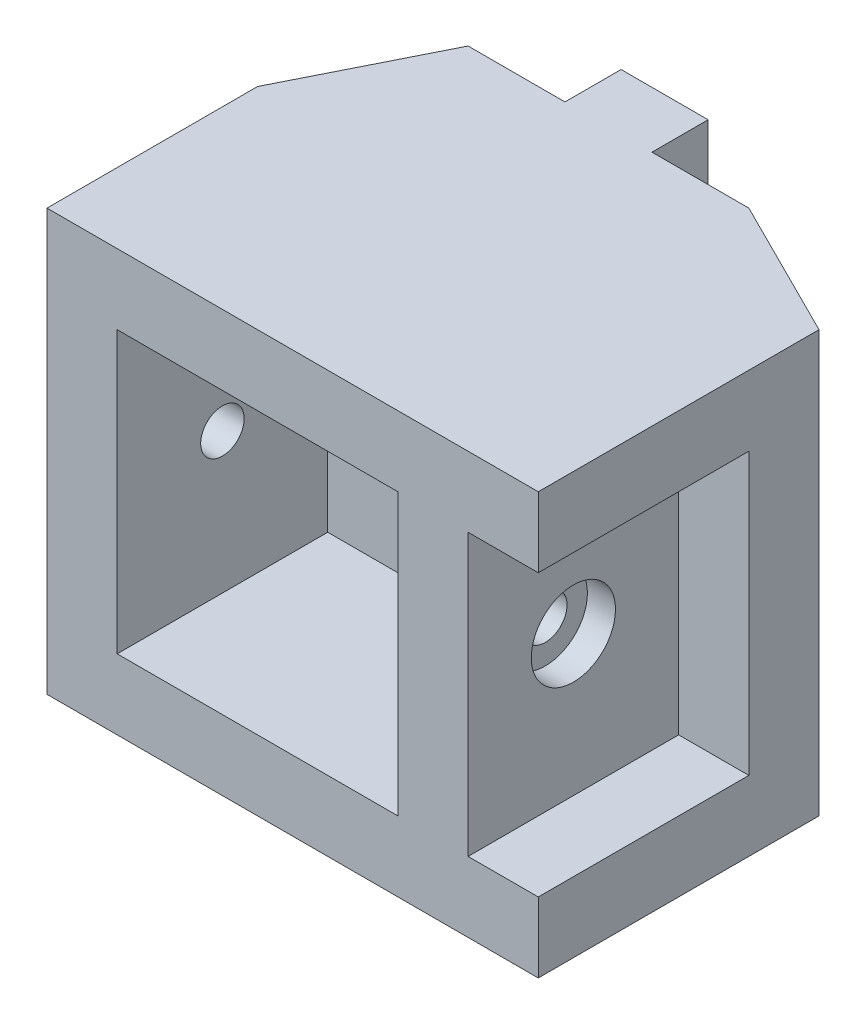
SolidWorks part; units mm, degrees
ref_plane "Front Plane" through (0, 0, 0) normal (0, 0, 1) x (1, 0, 0)
ref_plane "Top Plane" through (0, 0, 0) normal (0, 1, 0) x (1, 0, 0)
ref_plane "Right Plane" through (0, 0, 0) normal (1, 0, 0) x (0, 0, -1)
other "Configuration Table"
sketch "草图1" plane through (0, 0, 0) normal (0, 0, 1) x (1, 0, 0)
  line L0 (-15, 22) -> (-15, -22)
  line L1 (0, 22) -> (15, 22)
  line L2 (0, 22) -> (-15, 22)
  line L3 (15, 22) -> (15, -22)
  line L4 (15, -22) -> (-15, -22)
extrude "凸台-拉伸1" add sketch "草图1" along normal blind 14 contours L0 L4 L3 L1 L2
sketch "草图2" plane through (0, 22, 0) normal (0, 1, 0) x (1, 0, 0)
  line L3 (10, -4) -> (15, -14)
  line L4 (15, -14) -> (-15, -14)
  line L6 (-15, -14) -> (-10, -4)
  line L8 (3.1, -4) -> (3.1, 0)
  line L9 (-15, 0) -> (15, 0) construction
  line L10 (3.1, 0) -> (15, 0)
  line L11 (15, 0) -> (15, -14)
  line L12 (10, -4) -> (3.1, -4)
  line L13 (-3.1, -4) -> (-10, -4)
  line L14 (-15, -14) -> (-15, 0)
  line L15 (-15, 0) -> (-3.1, 0)
  line L16 (-3.1, 0) -> (-3.1, -4)
  line M14 (15, 0) -> (-15, 0)
  line M15 (-15, 0) -> (-15, -14)
  line M17 (15, -14) -> (15, 0)
extrude "切除-拉伸1" cut sketch "草图2" against normal blind 44 contours L16 L6 L13 M14 M15 | L12 L3 L8 M17 M14
sketch "草图3" plane through (0, 0, 0) normal (0, 0, -1) x (-1, 0, 0)
  line L2 (-3.1, 3.1) -> (-3.1, -3.1)
  line L4 (3.1, -22) -> (3.1, 22) construction
  line L5 (3.1, 3.1) -> (-3.1, 3.1)
  line L6 (-3.1, -22) -> (-3.1, 22) construction
  line L9 (-3.1, -3.1) -> (3.1, -3.1)
  line L10 (3.1, -22) -> (3.1, 22) construction
  line L11 (3.1, -3.1) -> (3.1, 3.1)
extrude "切除-拉伸2" cut sketch "草图3" against normal blind 4 contours L2 L9 L11 L5
sketch "草图4" plane through (0, 0, 14) normal (0, 0, 1) x (1, 0, 0)
  circle A0 centre (0, 0) radius 4
extrude "切除-拉伸3" cut sketch "草图4" against normal blind 5
sketch "草图5" plane through (0, 0, 9) normal (0, 0, 1) x (1, 0, 0)
  circle A0 centre (0, 0) radius 2.6
extrude "切除-拉伸4" cut sketch "草图5" against normal blind 5 contours A0
sketch "草图7" plane through (0, -22, 0) normal (0, -1, 0) x (1, 0, 0)
  line L3 (10, 4) -> (3.1, 4) construction
  line L5 (15, 14) -> (20, 14)
  line L8 (10, 4) -> (20, 9)
  line L9 (20, 9) -> (20, 14)
  line L10 (10, 4) -> (10, 14)
  line L11 (15, 14) -> (-15, 14) construction
  line L12 (10, 14) -> (15, 14)
extrude "凸台-拉伸2" add sketch "草图7" against normal blind 44 contours L12 L5 L9 L8 L10
sketch "草图8" plane through (0, 0, 14) normal (0, 0, 1) x (1, 0, 0)
  line L2 (-10, 10) -> (-10, 15)
  line L3 (-10, 10) -> (-15, 10)
  line L4 (0, 10) -> (10, 10)
  line L5 (10, 10) -> (10, 0)
  line L6 (0, -10) -> (10, -10)
  line L7 (10, -10) -> (10, 0)
  line L8 (0, -10) -> (-10, -10)
  line L9 (-10, -10) -> (-10, 0)
  line L10 (0, 10) -> (-10, 10)
  line L11 (-10, 10) -> (-10, 0)
  line L12 (-10, -10) -> (-10, -15)
  line L13 (-10, -10) -> (-15, -10)
  line L14 (10, -10) -> (15, -10)
  line L15 (10, -10) -> (10, -15)
  line L16 (10, 10) -> (10, 15)
  line L17 (10, 10) -> (15, 10)
  line L18 (-10, -15) -> (10, -15)
  line L19 (10, -15) -> (15, -15)
  line L20 (15, -15) -> (15, -10)
  line L21 (-15, -10) -> (-15, 10)
  line L22 (-10, 15) -> (10, 15)
  line L23 (15, 10) -> (15, 15)
  line L24 (15, 15) -> (10, 15)
  line L25 (15, 10) -> (15, -10)
  line L26 (-10, -15) -> (-15, -15)
  line L27 (-15, 22) -> (-15, -22) construction
  line L28 (-15, -15) -> (-15, -10)
  line L29 (-15, 10) -> (-15, 15)
  line L30 (-15, 15) -> (-10, 15)
  line L31 (15, -15) -> (20, -15)
  line L32 (20, 22) -> (20, -22) construction
  line L33 (20, -15) -> (20, -10)
  line L34 (20, -10) -> (15, -10)
  line L35 (15, 10) -> (20, 10)
  line L36 (20, 10) -> (20, 15)
  line L37 (20, 15) -> (15, 15)
  line M22 (-15, 22) -> (-15, -22)
  line M24 (20, -22) -> (20, 22)
extrude "凸台-拉伸4" add sketch "草图8" along normal blind 15 contours L26 L12 L13 M22 | L12 L18 L15 L6 L8 | L13 L9 L11 L3 M22 | L30 L3 L2 M22 | L22 L2 L10 L4 L16 | L23 L24 L16 L17 | L25 L17 L5 L7 L14 | L19 L20 L14 L15 | L34 L20 L31 M24 | L37 L23 L35 M24
sketch "草图9" plane through (0, 15, 0) normal (0, 1, 0) x (1, 0, 0)
  line L0 (20, -29) -> (20, -14) construction
  line L1 (-15, -29) -> (20, -29)
  line L2 (-15, -29) -> (-15, -24)
  line L3 (-15, -24) -> (20, -24)
  line L4 (20, -29) -> (20, -24)
extrude "凸台-拉伸5" add sketch "草图9" along normal blind 7 contours L2 L1 L4 L3
sketch "草图13" plane through (-10, 0, 0) normal (1, 0, 0) x (0, 0, -1)
  line L0 (-29, 10) -> (-14, -10)
  circle A0 centre (-21.5, 0) radius 1.55
extrude "切除-拉伸6" cut sketch "草图13" against normal blind 10 contours L0 A0 | L0 A0
sketch "草图14" plane through (-15, 0, 0) normal (-1, 0, 0) x (0, 0, 1)
  circle A0 centre (21.5, 0) radius 1.55
extrude "切除-拉伸7" cut sketch "草图14" against normal blind 30 contours A0
sketch "草图15" plane through (15, 0, 0) normal (1, 0, 0) x (0, 0, -1)
  circle A0 centre (-21.5, 0) radius 3
extrude "切除-拉伸8" cut sketch "草图15" against normal blind 2
sketch "草图16" plane through (-15, 0, 0) normal (-1, 0, 0) x (0, 0, 1)
  circle A0 centre (21.5, 0) radius 3
extrude "切除-拉伸9" cut sketch "草图16" against normal blind 2
sketch "草图17" plane through (0, 0, 29) normal (0, 0, 1) x (1, 0, 0)
  line L0 (20, 10) -> (20, 22) construction
  line L1 (-15, 22) -> (20, 22)
  line L2 (-15, 22) -> (-15, 15)
  line L3 (-15, 15) -> (20, 15)
  line L4 (20, 22) -> (20, 15)
extrude "切除-拉伸10" cut sketch "草图17" against normal blind 10
sketch "草图18" plane through (0, 0, 14) normal (0, 0, 1) x (1, 0, 0)
  line L1 (-15, 22) -> (20, 22)
  line L2 (-15, 22) -> (-15, 15)
  line L3 (-15, 15) -> (20, 15)
  line L4 (20, 22) -> (20, 15)
  line L5 (-15, -22) -> (20, -22)
  line L6 (-15, -22) -> (-15, -15)
  line L7 (-15, -15) -> (20, -15)
  line L8 (20, -22) -> (20, -15)
extrude "切除-拉伸11" cut sketch "草图18" against normal blind 20 contours L2 L1 L4 L3 | L6 L5 L8 L7
sketch "草图19" plane through (0, 0, 14) normal (0, 0, 1) x (1, 0, 0)
  circle A0 centre (0, 0) radius 5
extrude "切除-拉伸12" cut sketch "草图19" against normal blind 7
